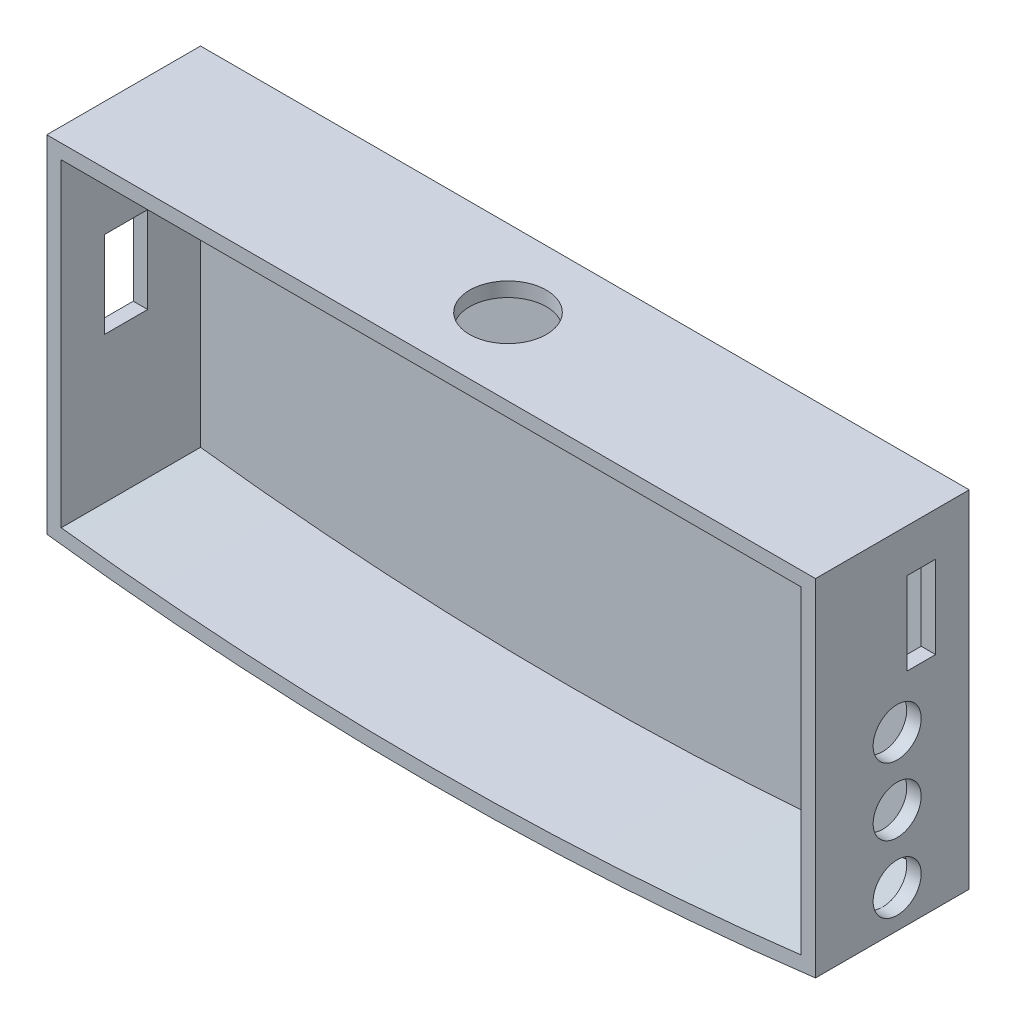
SolidWorks part; units mm, degrees
ref_plane "前视基准面" through (0, 0, 0) normal (0, 0, 1) x (1, 0, 0)
ref_plane "上视基准面" through (0, 0, 0) normal (0, 1, 0) x (1, 0, 0)
ref_plane "右视基准面" through (0, 0, 0) normal (1, 0, 0) x (0, 0, -1)
other "Configuration Table"
sketch "草图1" plane through (0, 0, 0) normal (0, 0, 1) x (1, 0, 0)
  line L1 (-10.4206, -29.6673) -> (-90.4206, -29.6673)
  line L2 (-10.4206, -29.6673) -> (-10.4206, 6.3327)
  line L3 (-10.4206, 6.3327) -> (-90.4206, 6.3327)
  line L4 (-90.4206, -29.6673) -> (-90.4206, 6.3327)
  line L5 (-10.4206, -29.6673) -> (-90.4206, 6.3327) construction
  line L6 (-10.4206, 6.3327) -> (-90.4206, -29.6673) construction
  arc A0 (-90.4206, -29.6673) -> (-10.4206, -29.6673) centre (-50.4206, 289.5866) ccw
  point P0 (-50.4206, -11.6673)
  dimension "D3" = 321.75
  dimension "D1" = 80
  dimension "D2" = 36
extrude "凸台-拉伸1" add sketch "草图1" along normal blind 16 contours L4 L1 L2 L3 | L1 A0
shell "抽壳1" thickness 1.5
sketch "草图2" plane through (-90.4206, 0, 0) normal (-1, 0, 0) x (0, 0, 1)
  line L6 (0, -29.6673) -> (0, 6.3327) construction
  line L7 (7, -4.1673) -> (11.5, -4.1673)
  line L8 (7, -4.1673) -> (7, -13.1673)
  line L9 (7, -13.1673) -> (11.5, -13.1673)
  line L10 (11.5, -4.1673) -> (11.5, -13.1673)
  line L11 (16, 6.3327) -> (0, 6.3327) construction
  dimension "D1" = 4.5
  dimension "D2" = 9
  dimension "D3" = 10.5
  dimension "D9" = 7
extrude "切除-拉伸3" cut sketch "草图2" against normal up to next
sketch "草图6" plane through (-10.4206, 0, 0) normal (1, 0, 0) x (0, 0, -1)
  line L1 (-6.5, 1.8327) -> (-3.5, 1.8327)
  line L2 (-6.5, 1.8327) -> (-6.5, -6.7673)
  line L3 (-6.5, -6.7673) -> (-3.5, -6.7673)
  line L4 (-3.5, 1.8327) -> (-3.5, -6.7673)
  line L8 (-16, 6.3327) -> (0, 6.3327) construction
  line L11 (0, -29.6673) -> (0, 6.3327) construction
  circle A0 centre (-7.5, -11.7673) radius 2.5
  circle A1 centre (-7.5, -18.7673) radius 2.5
  circle A2 centre (-7.5, -25.7673) radius 2.5
  dimension "D5" = 5
  dimension "D6" = 5
  dimension "D7" = 5
  dimension "D1" = 3
  dimension "D2" = 8.6
  dimension "D3" = 7.5
  dimension "D4" = 4.5
  dimension "D8" = 5
  dimension "D9" = 7
  dimension "D10" = 7
  dimension "D11" = 3.5
extrude "切除-拉伸4" cut sketch "草图6" against normal up to next
sketch "草图7" plane through (0, 6.3327, 0) normal (0, 1, 0) x (1, 0, 0)
  line L0 (-10.4206, 0) -> (-90.4206, 0) construction
  line L1 (-10.4206, -16) -> (-10.4206, 0) construction
  circle A0 centre (-50.4206, -8) radius 4
  dimension "D1" = 8
  dimension "D3" = 8
  dimension "D2" = 40
extrude "切除-拉伸5" cut sketch "草图7" against normal blind 2
